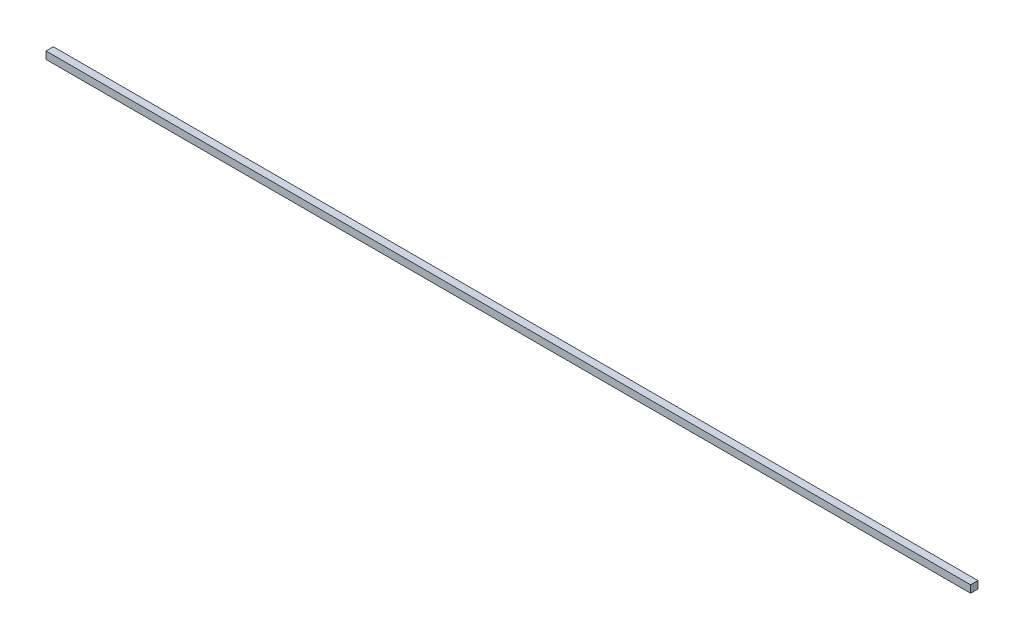
SolidWorks part; units mm, degrees
ref_plane "Ebene vorne" through (0, 0, 0) normal (0, 0, 1) x (1, 0, 0)
ref_plane "Ebene oben" through (0, 0, 0) normal (0, 1, 0) x (1, 0, 0)
ref_plane "Ebene rechts" through (0, 0, 0) normal (1, 0, 0) x (0, 0, -1)
sketch "Skizze1" plane through (0, 0, 0) normal (0, 1, 0) x (1, 0, 0)
  line L1 (0, 0) -> (5035, 0)
  line L2 (0, 0) -> (0, 40)
  line L3 (0, 40) -> (5035, 40)
  line L4 (5035, 0) -> (5035, 40)
  dimension "D1" = 5035
  dimension "D2" = 40
extrude "Aufsatz-Linear austragen1" add sketch "Skizze1" along normal blind 40
